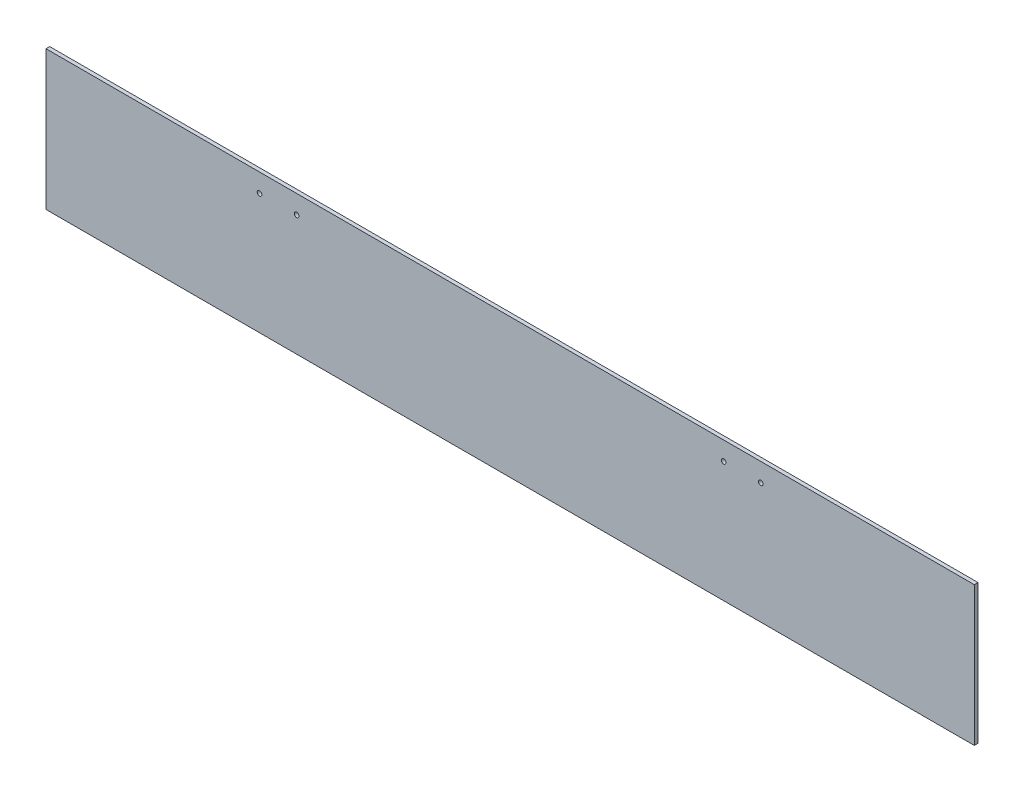
SolidWorks part; units mm, degrees
ref_plane "Front Plane" through (0, 0, 0) normal (0, 0, 1) x (1, 0, 0)
ref_plane "Top Plane" through (0, 0, 0) normal (0, 1, 0) x (1, 0, 0)
ref_plane "Right Plane" through (0, 0, 0) normal (1, 0, 0) x (0, 0, -1)
sketch "Sketch2" plane through (0, 0, 0) normal (0, 0, 1) x (1, 0, 0)
  line L1 (500, 150) -> (-500, 150)
  line L2 (500, 150) -> (500, 0)
  line L3 (500, 0) -> (-500, 0)
  line L4 (-500, 150) -> (-500, 0)
  line L5 (500, 150) -> (-500, 0) construction
  line L6 (500, 0) -> (-500, 150) construction
  point P0 (0, 75)
  point P5 (0, 0)
  dimension "D1" = 150
  dimension "D2" = 1000
extrude "Boss-Extrude1" add sketch "Sketch2" along normal mid plane 4
sketch "Sketch3" plane through (0, 0, 2) normal (0, 0, 1) x (1, 0, 0)
  line L0 (-415.4141, 130) -> (415.4141, 130) construction
  line L1 (500, 150) -> (-500, 150) construction
  line L2 (0, 211.2276) -> (0, -123.4115) construction
  line L3 (-500, 150) -> (-500, 0) construction
  point P2 (0, 130)
  point P8 (-270, 130)
  point P9 (-230, 130)
  point P14 (230, 130)
  point P15 (270, 130)
  point P16 (-270, 130)
  point P18 (-230, 130)
  point P20 (230, 130)
  point P22 (270, 130)
  dimension "D1" = 20
  dimension "D2" = 40
  dimension "D3" = 230
hole_wizard "Tap Drill for M6 Tap1" positions "Sketch3" profile "Sketch4" hole size "M6" standard "ISO" end condition through all
sketch "Sketch4" plane through (270, 130, 2) normal (1, 0, 0) x (0, -1, 0)
  line L0 (0, 0) -> (0, 4)
  line L1 (0, 4) -> (2.5, 4)
  line L2 (2.5, 4) -> (2.5, 0)
  line L5 (2.5, 0) -> (0, 0)
  line L11 (0, -6.35) -> (0, 107.95) construction
  dimension "Thru Hole Dia." = 5
  dimension "Thru Hole Depth" = 4
